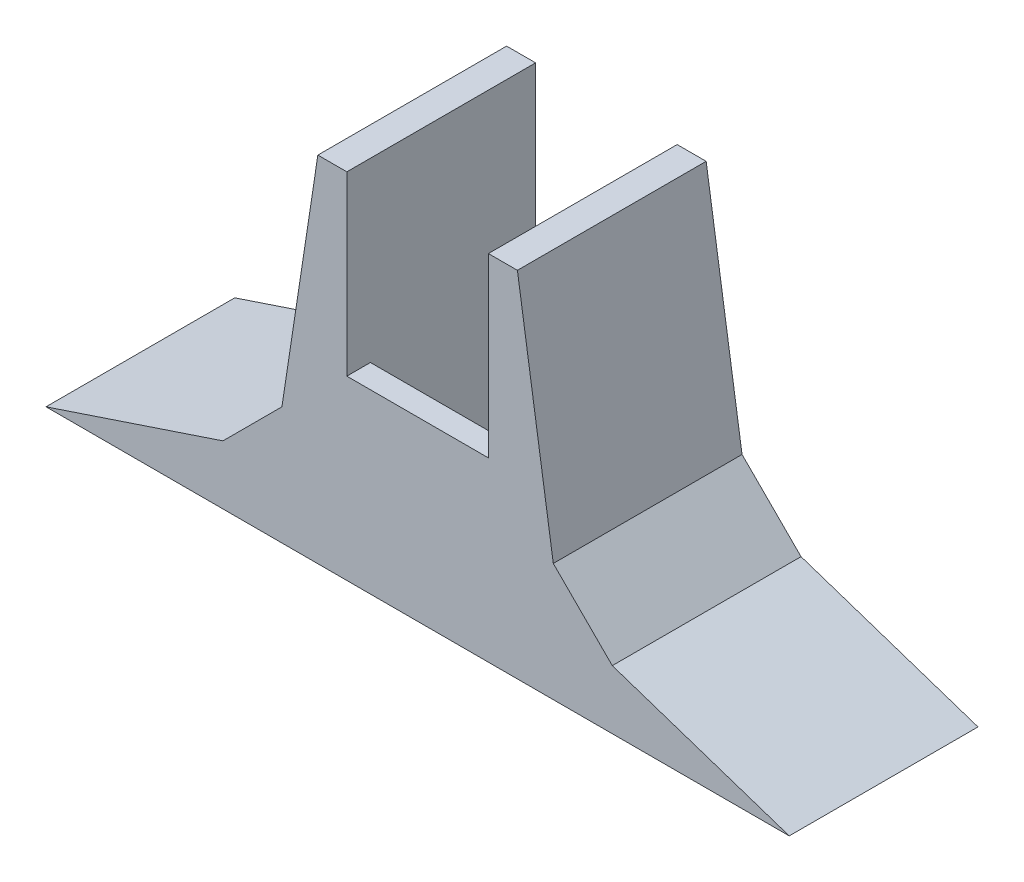
SolidWorks part; units mm, degrees
ref_plane "정면" through (0, 0, 0) normal (0, 0, 1) x (1, 0, 0)
ref_plane "윗면" through (0, 0, 0) normal (0, 1, 0) x (1, 0, 0)
ref_plane "우측면" through (0, 0, 0) normal (1, 0, 0) x (0, 0, -1)
sketch "스케치1" plane through (0, 0, 0) normal (0, 0, 1) x (1, 0, 0)
  line L0 (0, 0) -> (0, 30) construction
  line L1 (31.5, 0) -> (-31.5, 0)
  line L2 (-31.5, 0) -> (-16.5, 5)
  line L3 (31.5, 0) -> (16.5, 5)
  line L4 (-16.5, 5) -> (-11.5, 10)
  line L5 (16.5, 5) -> (11.5, 10)
  line L6 (-11.5, 10) -> (-8.4575, 30)
  line L7 (11.5, 10) -> (8.4575, 30)
  line L8 (-8.4575, 30) -> (8.4575, 30)
  dimension "D1" = 63
  dimension "D2" = 30
  dimension "D3" = 15
  dimension "D4" = 5
  dimension "D5" = 5
  dimension "D6" = 5
extrude "보스-돌출2" add sketch "스케치1" along normal blind 16 contours L8 L7 L5 L3 L1 L2 L4 L6
sketch "스케치3" plane through (0, 30, 0) normal (0, 1, 0) x (1, 0, 0)
  line L0 (0, 0) -> (0, -16) construction
  line L1 (-8.4575, -16) -> (8.4575, -16) construction
  line L2 (-8.4575, -8) -> (8.4575, -8) construction
  line L3 (-8.4575, -16) -> (-8.4575, 0) construction
  line L4 (8.4575, -16) -> (8.4575, 0) construction
  line L6 (-6, -14) -> (6, -14)
  line L7 (-6, -14) -> (-6, -2)
  line L8 (-6, -2) -> (6, -2)
  line L9 (6, -14) -> (6, -2)
  line L10 (0, -2) -> (0, -14) construction
  line L11 (-6, -8) -> (6, -8) construction
  point P11 (0, -8)
  dimension "D1" = 12
  dimension "D2" = 12
extrude "컷-돌출3" cut sketch "스케치3" against normal blind 25 contours L9 L8 L7 L6
sketch "스케치6" plane through (0, 0, 16) normal (0, 0, 1) x (1, 0, 0)
  line L0 (0, 0) -> (0, 30) construction
  line L1 (-8.4575, 30) -> (8.4575, 30) construction
  line L2 (0, 30) -> (0, 15) construction
  line L3 (0, 15) -> (-10.7394, 15) construction
  line L4 (-11.5, 10) -> (-8.4575, 30) construction
  line L5 (-10.7394, 15) -> (10.7394, 15) construction
  line L6 (11.5, 10) -> (8.4575, 30) construction
  line L8 (0, 15) -> (6, 15)
  line L9 (0, 15) -> (0, 30)
  line L10 (0, 30) -> (6, 30)
  line L11 (6, 15) -> (6, 30)
  line L12 (0, 15) -> (-6, 15)
  line L13 (0, 15) -> (0, 30)
  line L14 (0, 30) -> (-6, 30)
  line L15 (-6, 15) -> (-6, 30)
  line M10 (8.4575, 30) -> (-8.4575, 30)
  dimension "D1" = 6
  dimension "D2" = 6
extrude "컷-돌출4" cut sketch "스케치6" against normal blind 25 contours L8 L11 L9 M10 | L15 L12 L9 M10
